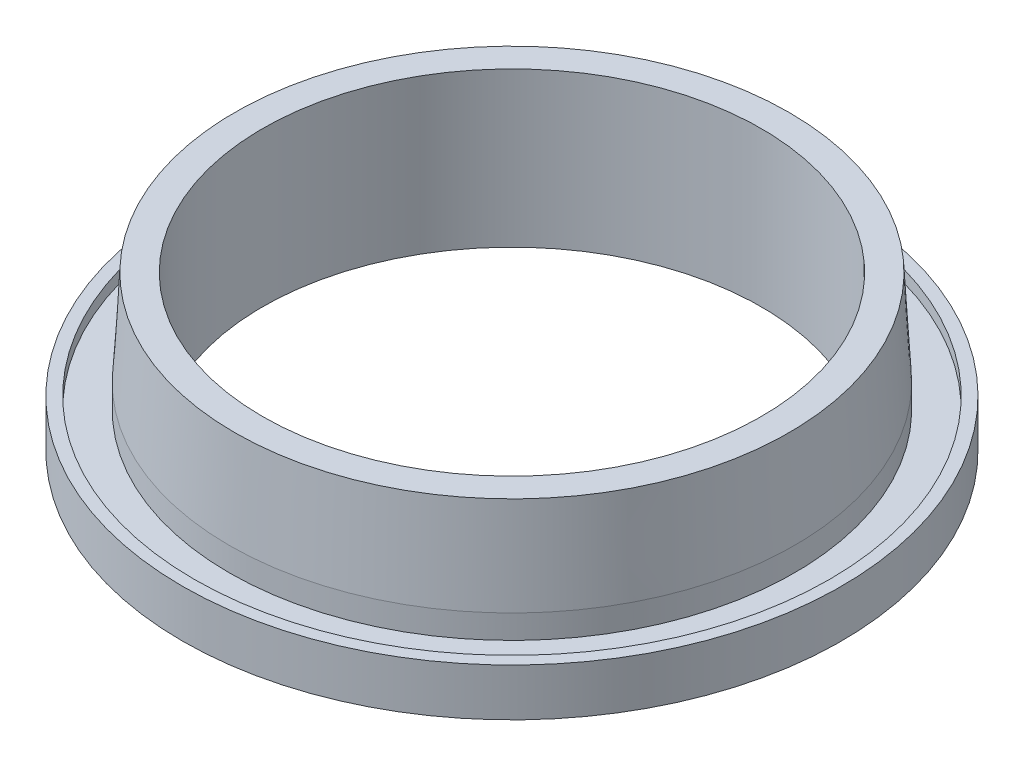
SolidWorks part; units mm, degrees
ref_plane "Front Plane" through (0, 0, 0) normal (0, 0, 1) x (1, 0, 0)
ref_plane "Top Plane" through (0, 0, 0) normal (0, 1, 0) x (1, 0, 0)
ref_plane "Right Plane" through (0, 0, 0) normal (1, 0, 0) x (0, 0, -1)
sketch "Sketch1" plane through (0, 0, 0) normal (0, 1, 0) x (1, 0, 0)
  circle A0 centre (0, 0) radius 69.375
  circle A1 centre (0, 0) radius 66.875
  dimension "D1" = 138.75
  dimension "D2" = 133.75
extrude "Boss-Extrude1" add sketch "Sketch1" along normal blind 2.5
sketch "Sketch2" plane through (0, 0, 0) normal (0, 1, 0) x (1, 0, 0)
  circle A1 centre (0, 0) radius 69.375
  circle A2 centre (0, 0) radius 69.375
  dimension "D1" = 0
extrude "Boss-Extrude2" add sketch "Sketch2" against normal blind 7.5
sketch "Sketch3" plane through (0, 0, 0) normal (0, 1, 0) x (1, 0, 0)
  circle A0 centre (0, 0) radius 59.5
  dimension "D1" = 119
extrude "Boss-Extrude3" add sketch "Sketch3" along normal blind 25
chamfer "Chamfer1" distance 20 angle 3.25 1 edges at (0, 25, 59.5)
sketch "Sketch4" plane through (0, 25, 0) normal (0, 1, 0) x (1, 0, 0)
  circle A0 centre (0, 0) radius 52.5
  dimension "D1" = 105
extrude "Cut-Extrude1" cut sketch "Sketch4" against normal through all both and the other way through all
